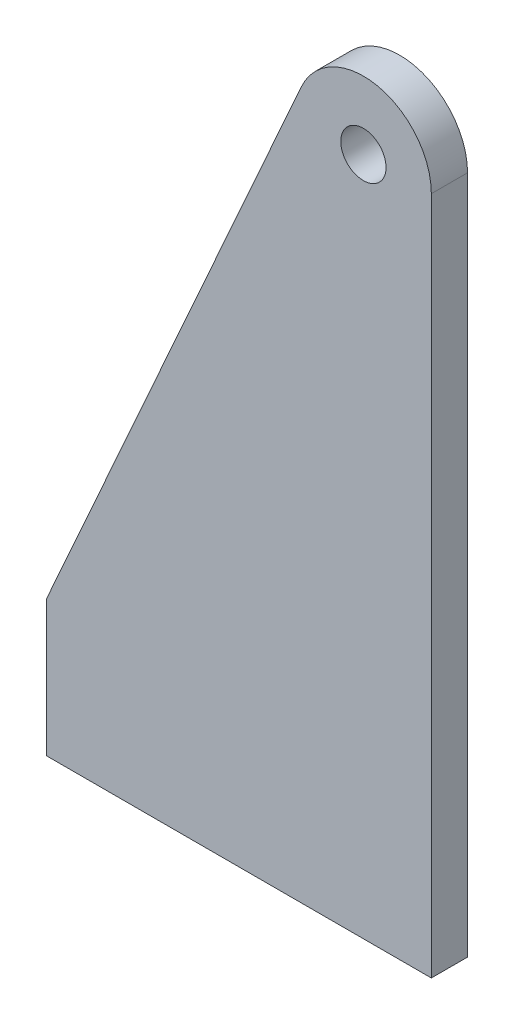
SolidWorks part; units mm, degrees
ref_plane "正面" through (0, 0, 0) normal (0, 0, 1) x (1, 0, 0)
ref_plane "平面" through (0, 0, 0) normal (0, 1, 0) x (1, 0, 0)
ref_plane "右側面" through (0, 0, 0) normal (1, 0, 0) x (0, 0, -1)
sketch "ｽｹｯﾁ1" plane through (0, 0, 0) normal (0, 0, 1) x (1, 0, 0)
  line L0 (0, 0) -> (0, 150)
  line L1 (-28.697, 156.1149) -> (-85, 30)
  line L2 (-85, 30) -> (-85, 0)
  line L3 (-85, 0) -> (0, 0)
  arc A0 (0, 150) -> (-28.697, 156.1149) centre (-15, 150) ccw
  circle A1 centre (-15, 150) radius 5
  dimension "D4" = 15
  dimension "D5" = 10
  dimension "D1" = 150
  dimension "D2" = 30
  dimension "D3" = 85
extrude "ﾎﾞｽ - 押し出し1" add sketch "ｽｹｯﾁ1" along normal blind 8
